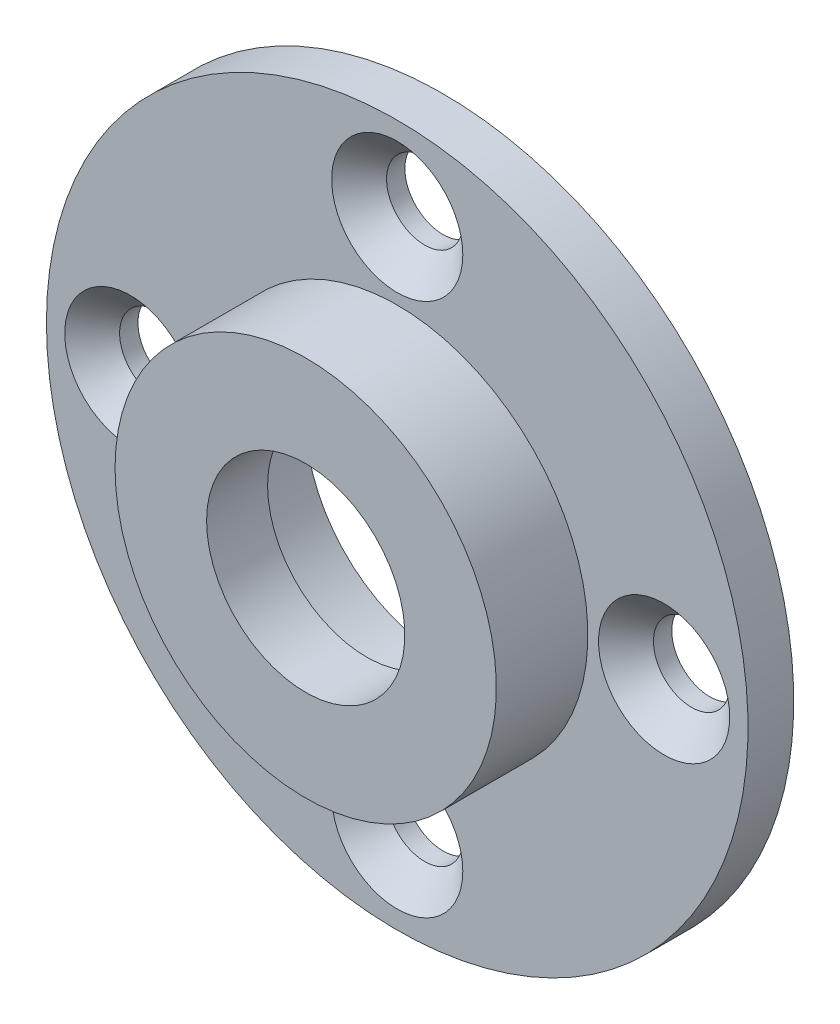
SolidWorks part; units mm, degrees
ref_plane "Piano frontale" through (0, 0, 0) normal (0, 0, 1) x (1, 0, 0)
ref_plane "Piano superiore" through (0, 0, 0) normal (0, 1, 0) x (1, 0, 0)
ref_plane "Piano destro" through (0, 0, 0) normal (1, 0, 0) x (0, 0, -1)
sketch "Schizzo1" plane through (0, 0, 0) normal (0, 1, 0) x (1, 0, 0)
  line L0 (0, 7.5743) -> (0, 0) construction
  line L1 (0, 0) -> (6.5, 0) construction
  line L2 (6.5, 0) -> (6.5, 4)
  line L3 (6.5, 4) -> (9, 4)
  line L4 (9, 4) -> (9, 9)
  line L5 (9, 9) -> (23, 9)
  line L6 (23, 9) -> (23, 6)
  line L7 (23, 6) -> (12.5, 6)
  line L8 (12.5, 6) -> (12.5, 0)
  line L9 (12.5, 0) -> (6.5, 0)
  point P3 (0, 0)
  point P12 (6, 2.5743)
  point P13 (11.7162, 3.4662)
  point P14 (0, 7.5743)
  point P15 (6.5, 0)
  dimension "D1" = 18
  dimension "D2" = 46
  dimension "D3" = 13
  dimension "D4" = 25
  dimension "D5" = 5
  dimension "D6" = 9
  dimension "D7" = 6
revolve "Rivoluzione1" add sketch "Schizzo1" angle 360 about L0
hole_wizard "Foro svasato per Vite M6-2" positions "Schizzo3D3" profile "Schizzo4" countersink size "M6" standard "ISO" end condition up to next
sketch3d "Schizzo3D3"
  line L0 (0, 0, 0) -> (0, 0, -6) construction
  line L1 (0, 0, -6) -> (0, 0, -9) construction
  line L2 (0, 0, 0) -> (0, 0, -6) construction
  line L4 (17.5, 0, -6) -> (-17.5, 0, -6) construction
  line L6 (0, 0, -6) -> (0, 17.5, -6) construction
  circle A0 centre (0, 0, -6) radius 17.5 construction
  point P10 (0, 0, 11.5)
  point P23 (0, 17.5, -6)
  dimension "D2" = 35
sketch "Schizzo4" plane through (0, 17.5, -6) normal (1, 0, 0) x (0, -1, 0)
  line L0 (0, 0) -> (0, 3)
  line L1 (0, 3) -> (2.5, 3)
  line L2 (2.5, 3) -> (2.5, 1.8)
  line L3 (2.5, 1.8) -> (4.3, 0)
  line L5 (4.3, 0) -> (0, 0)
  line L6 (-2.5, 1.8) -> (-4.3, 0) construction
  line L11 (0, -6.35) -> (0, 107.95) construction
  dimension "Thru Hole Dia." = 5
  dimension "Thru Hole Depth" = 3
  dimension "Near C'Sink Dia." = 8.6
  dimension "Near C'Sink Angle" = 90
pattern_circular "RipetizioneCircolare1" count 4 over 360 about axis through (0, 0, 0) along (0, 0, 1) of "Foro svasato per Vite M6-2"
